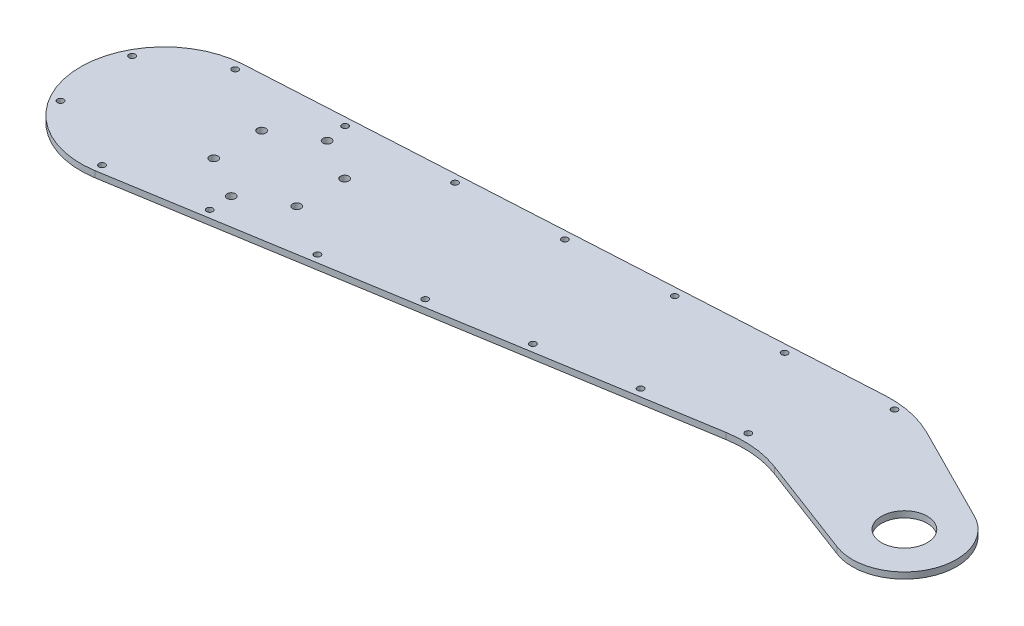
SolidWorks part; units mm, degrees
ref_plane "Front Plane" through (0, 0, 0) normal (0, 0, 1) x (1, 0, 0)
ref_plane "Top Plane" through (0, 0, 0) normal (0, 1, 0) x (1, 0, 0)
ref_plane "Right Plane" through (0, 0, 0) normal (1, 0, 0) x (0, 0, -1)
sketch "Sketch1" plane through (0, 0, 0) normal (0, 1, 0) x (1, 0, 0)
  line L0 (0, 0) -> (300, 0) construction
  line L1 (0, 0) -> (0, 37.5) construction
  line L2 (-2.1002, 37.4411) -> (6.0625, -37.0067) construction
  line L3 (311.2679, 22.3167) -> (291.1646, -23.3867) construction
  line L4 (300, 0) -> (300, 25) construction
  line L5 (-2.1002, 37.4411) -> (701.376, 76.9007)
  line L6 (701.376, 76.9007) -> (6.0625, -37.0067)
  line L7 (291.1646, -23.3867) -> (230.0775, -0.3082)
  line L8 (311.2679, 22.3167) -> (252.9755, 51.7489)
  line L9 (252.9755, 51.7489) -> (230.0775, -0.3082) construction
  line L10 (-2.1002, 37.4411) -> (-51.9511, 34.6449)
  line L11 (-43.21, -45.0786) -> (6.0625, -37.0067)
  line L12 (-49.7021, -5.4495) -> (0, 0) construction
  line L13 (0, 0) -> (701.376, 76.9007) construction
  circle A0 centre (0, 0) radius 37.5
  circle A1 centre (300, 0) radius 11
  circle A2 centre (300, 0) radius 25
  circle A3 centre (0, 0) radius 23 construction
  circle A4 centre (0, 23) radius 2
  circle A5 centre (19.9186, 11.5) radius 2
  circle A6 centre (19.9186, -11.5) radius 2
  circle A7 centre (0, -23) radius 2
  circle A8 centre (-19.9186, -11.5) radius 2
  circle A9 centre (-19.9186, 11.5) radius 2
  arc A10 (-51.9511, 34.6449) -> (-43.21, -45.0786) centre (-49.7021, -5.4495) ccw
  point P11 (325.211, 15.2767)
  point P31 (0, 0)
  dimension "D2" = 75
  dimension "D3" = 22
  dimension "D4" = 50
  dimension "D7" = 46
  dimension "D8" = 4
  dimension "D1" = 300
  dimension "D5" = 150
  dimension "D6" = 150
  dimension "D9" = 6
  dimension "D10" = 50
extrude "Boss-Extrude2" add sketch "Sketch1" along normal blind 3 contours A0 A3 | A2 L8 L5 A0 L6 | A2 L6 L7 | L6 A2 | L6 A2 A1 | L10 A10 L11 A0
fillet "Fillet1" radius 50 2 edges at (230.0775, 1.5, 0.3082) (252.9755, 1.5, -51.7489)
sketch "Sketch3" plane through (0, 3, 0) normal (0, 1, 0) x (1, 0, 0)
  line L0 (-49.6973, -5.493) -> (0, 0)
  line L1 (0, 0) -> (496.9735, 54.9302)
  dimension "D1" = 500
sketch "Sketch2" plane through (0, 3, 0) normal (0, 1, 0) x (1, 0, 0)
  line L0 (-51.7271, 30.6512) -> (238.7529, 46.9449) construction
  line L1 (-43.8567, -41.1312) -> (227.7136, 3.3579) construction
  line L2 (216.8562, -2.4741) -> (-43.21, -45.0786) construction
  line L3 (-51.9511, 34.6449) -> (239.599, 50.9986) construction
  line L4 (264.0889, 41.6567) -> (301.3029, 22.8671) construction
  line L5 (311.2679, 22.3167) -> (264.935, 45.7105) construction
  line L6 (239.599, 50.9986) -> (-51.9511, 34.6449) construction
  line L7 (-43.21, -45.0786) -> (216.8562, -2.4741) construction
  line L8 (-51.7271, 30.6512) -> (-49.7021, -5.4495) construction
  circle A0 centre (-49.7021, -5.4495) radius 36.1574 construction
  arc A24 (-51.9511, 34.6449) -> (-43.21, -45.0786) centre (-49.7021, -5.4495) ccw construction
  arc A25 (238.7529, 46.9449) -> (264.0889, 41.6567) centre (241.5532, -2.9767) cw construction
  circle A26 centre (-51.7271, 30.6512) radius 1.5
  circle A27 centre (-43.8567, -41.1312) radius 1.5
  circle A31 centre (-80.543, -24.3567) radius 1.5
  circle A32 centre (-82.0145, 11.4657) radius 1.5
  circle A33 centre (-48.7842, -40.9936) radius 1.5 [skipped]
  circle A34 centre (-18.4969, -21.8081) radius 1.5 [skipped]
  circle A35 centre (-19.9683, 14.0143) radius 1.5 [skipped]
  circle A36 centre (-1.8056, 33.4514) radius 1.5
  circle A37 centre (48.1159, 36.2516) radius 1.5
  circle A38 centre (98.0375, 39.0518) radius 1.5
  circle A39 centre (147.959, 41.852) radius 1.5
  circle A40 centre (197.8805, 44.6522) radius 1.5
  circle A41 centre (247.802, 47.4524) radius 1.5
  circle A48 centre (0.5513, -33.8562) radius 1.5
  circle A49 centre (44.9594, -26.5812) radius 1.5
  circle A50 centre (89.3674, -19.3062) radius 1.5
  circle A51 centre (133.7755, -12.0312) radius 1.5
  circle A52 centre (178.1835, -4.7562) radius 1.5
  circle A53 centre (222.5916, 2.5188) radius 1.5
  point P29 (0, 0)
  point P32 (-50.2557, -5.1712)
  dimension "D1" = 4
  dimension "D2" = 4
  dimension "D3" = 4
  dimension "D4" = 50
  dimension "D6" = 3
  dimension "D5" = 4
  dimension "D7" = 6
  dimension "D8" = 7
  dimension "D9" = 7
extrude "Cut-Extrude1" cut sketch "Sketch2" against normal blind 10
